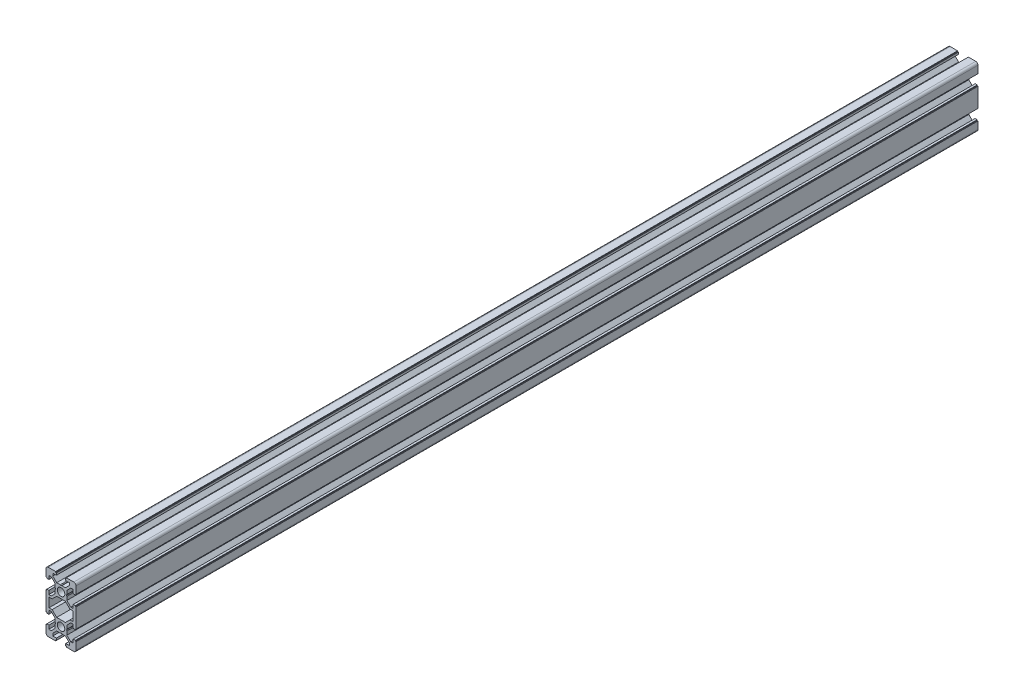
SolidWorks part; units mm, degrees
ref_plane "前视基准面" through (0, 0, 0) normal (0, 0, 1) x (1, 0, 0)
ref_plane "上视基准面" through (0, 0, 0) normal (0, 1, 0) x (1, 0, 0)
ref_plane "右视基准面" through (0, 0, 0) normal (1, 0, 0) x (0, 0, -1)
sketch "草图30" plane through (0, 0, 0) normal (0, 0, 1) x (1, 0, 0)
  line B0 (-7.4456, 0) -> (7.4456, 0) construction
  line B1 (0, -11.0182) -> (0, 30.6964) construction
  line B2 (-7.4456, 20) -> (7.4456, 20) construction
  line B3 (-10.5248, 9.8391) -> (10.5248, 9.8391) construction
  line B4 (5.9101, 6.9) -> (2.9101, 3.9)
  line B5 (2.9101, 3.9) -> (-2.9101, 3.9)
  line B6 (-2.9101, 3.9) -> (-5.9101, 6.9)
  line B7 (-5.9101, 6.9) -> (-8, 6.9)
  line B8 (-8, 6.9) -> (-8, 13.1)
  line B9 (-8, 13.1) -> (-5.9101, 13.1)
  line B10 (-5.9101, 13.1) -> (-2.9101, 16.1)
  line B11 (-2.9101, 16.1) -> (2.9101, 16.1)
  line B12 (2.9101, 16.1) -> (5.9101, 13.1)
  line B13 (5.9101, 13.1) -> (8, 13.1)
  line B14 (8, 13.1) -> (8, 6.9)
  line B15 (8, 6.9) -> (5.9101, 6.9)
  line B16 (-8.1, 14.5) -> (-8.1, 16.9)
  line B17 (-8.1, 16.9) -> (-9.5, 16.9)
  line B18 (-9.5, 16.9) -> (-9.5, 16.4)
  line B19 (-9.5, 16.4) -> (-10, 16.4)
  line B20 (-10, 16.4) -> (-10, 3.6)
  line B21 (-10, 3.6) -> (-9.5, 3.6)
  line B22 (-9.5, 3.6) -> (-9.5, 3.1)
  line B23 (-9.5, 3.1) -> (-8.1, 3.1)
  line B24 (-8.1, 3.1) -> (-8.1, 5.5)
  line B25 (-8.1, 5.5) -> (-6.4899, 5.5)
  line B26 (-6.4899, 5.5) -> (-3.9, 2.9101)
  line B27 (-3.9, 2.9101) -> (-3.9, 0.5196)
  line B28 (-3.9, 0.5196) -> (-3.6, 0)
  line B29 (-3.6, 0) -> (-3.9, -0.5196)
  line B30 (-3.9, -0.5196) -> (-3.9, -2.9101)
  line B31 (-3.9, -2.9101) -> (-6.4899, -5.5)
  line B32 (-6.4899, -5.5) -> (-8.1, -5.5)
  line B33 (-8.1, -5.5) -> (-8.1, -3.1)
  line B34 (-8.1, -3.1) -> (-9.5, -3.1)
  line B35 (-9.5, -3.1) -> (-9.5, -3.6)
  line B36 (-9.5, -3.6) -> (-10, -3.6)
  line B37 (-10, -3.6) -> (-10, -8.5)
  line B38 (-8.5, -10) -> (-3.6, -10)
  line B39 (-3.6, -10) -> (-3.6, -9.5)
  line B40 (-3.6, -9.5) -> (-3.1, -9.5)
  line B41 (-3.1, -9.5) -> (-3.1, -8.1)
  line B42 (-3.1, -8.1) -> (-5.5, -8.1)
  line B43 (-5.5, -8.1) -> (-5.5, -6.4899)
  line B44 (-5.5, -6.4899) -> (-2.9101, -3.9)
  line B45 (-2.9101, -3.9) -> (-0.5196, -3.9)
  line B46 (-0.5196, -3.9) -> (0, -3.6)
  line B47 (0, -3.6) -> (0.5196, -3.9)
  line B48 (0.5196, -3.9) -> (2.9101, -3.9)
  line B49 (2.9101, -3.9) -> (5.5, -6.4899)
  line B50 (5.5, -6.4899) -> (5.5, -8.1)
  line B51 (5.5, -8.1) -> (3.1, -8.1)
  line B52 (3.1, -8.1) -> (3.1, -9.5)
  line B53 (3.1, -9.5) -> (3.6, -9.5)
  line B54 (3.6, -9.5) -> (3.6, -10)
  line B55 (3.6, -10) -> (8.5, -10)
  line B56 (10, -8.5) -> (10, -3.6)
  line B57 (10, -3.6) -> (9.5, -3.6)
  line B58 (9.5, -3.6) -> (9.5, -3.1)
  line B59 (9.5, -3.1) -> (8.1, -3.1)
  line B60 (8.1, -3.1) -> (8.1, -5.5)
  line B61 (8.1, -5.5) -> (6.4899, -5.5)
  line B62 (6.4899, -5.5) -> (3.9, -2.9101)
  line B63 (3.9, -2.9101) -> (3.9, -0.5196)
  line B64 (3.9, -0.5196) -> (3.6, 0)
  line B65 (3.6, 0) -> (3.9, 0.5196)
  line B66 (3.9, 0.5196) -> (3.9, 2.9101)
  line B67 (3.9, 2.9101) -> (6.4899, 5.5)
  line B68 (6.4899, 5.5) -> (8.1, 5.5)
  line B69 (8.1, 5.5) -> (8.1, 3.1)
  line B70 (8.1, 3.1) -> (9.5, 3.1)
  line B71 (9.5, 3.1) -> (9.5, 3.6)
  line B72 (9.5, 3.6) -> (10, 3.6)
  line B73 (10, 3.6) -> (10, 16.4)
  line B74 (10, 16.4) -> (9.5, 16.4)
  line B75 (9.5, 16.4) -> (9.5, 16.9)
  line B76 (9.5, 16.9) -> (8.1, 16.9)
  line B77 (8.1, 16.9) -> (8.1, 14.5)
  line B78 (8.1, 14.5) -> (6.4899, 14.5)
  line B79 (6.4899, 14.5) -> (3.9, 17.0899)
  line B80 (3.9, 17.0899) -> (3.9, 19.4804)
  line B81 (3.9, 19.4804) -> (3.6, 20)
  line B82 (3.6, 20) -> (3.9, 20.5196)
  line B83 (3.9, 20.5196) -> (3.9, 22.9101)
  line B84 (3.9, 22.9101) -> (6.4899, 25.5)
  line B85 (6.4899, 25.5) -> (8.1, 25.5)
  line B86 (8.1, 25.5) -> (8.1, 23.1)
  line B87 (8.1, 23.1) -> (9.5, 23.1)
  line B88 (9.5, 23.1) -> (9.5, 23.6)
  line B89 (9.5, 23.6) -> (10, 23.6)
  line B90 (10, 23.6) -> (10, 28.5)
  line B91 (8.5, 30) -> (3.6, 30)
  line B92 (3.6, 30) -> (3.6, 29.5)
  line B93 (3.6, 29.5) -> (3.1, 29.5)
  line B94 (3.1, 29.5) -> (3.1, 28.1)
  line B95 (3.1, 28.1) -> (5.5, 28.1)
  line B96 (5.5, 28.1) -> (5.5, 26.4899)
  line B97 (5.5, 26.4899) -> (2.9101, 23.9)
  line B98 (2.9101, 23.9) -> (0.5196, 23.9)
  line B99 (0.5196, 23.9) -> (0, 23.6)
  line B100 (0, 23.6) -> (-0.5196, 23.9)
  line B101 (-0.5196, 23.9) -> (-2.9101, 23.9)
  line B102 (-2.9101, 23.9) -> (-5.5, 26.4899)
  line B103 (-5.5, 26.4899) -> (-5.5, 28.1)
  line B104 (-5.5, 28.1) -> (-3.1, 28.1)
  line B105 (-3.1, 28.1) -> (-3.1, 29.5)
  line B106 (-3.1, 29.5) -> (-3.6, 29.5)
  line B107 (-3.6, 29.5) -> (-3.6, 30)
  line B108 (-3.6, 30) -> (-8.5, 30)
  line B109 (-10, 28.5) -> (-10, 23.6)
  line B110 (-10, 23.6) -> (-9.5, 23.6)
  line B111 (-9.5, 23.6) -> (-9.5, 23.1)
  line B112 (-9.5, 23.1) -> (-8.1, 23.1)
  line B113 (-8.1, 23.1) -> (-8.1, 25.5)
  line B114 (-8.1, 25.5) -> (-6.4899, 25.5)
  line B115 (-6.4899, 25.5) -> (-3.9, 22.9101)
  line B116 (-3.9, 22.9101) -> (-3.9, 20.5196)
  line B117 (-3.9, 20.5196) -> (-3.6, 20)
  line B118 (-3.6, 20) -> (-3.9, 19.4804)
  line B119 (-3.9, 19.4804) -> (-3.9, 17.0899)
  line B120 (-3.9, 17.0899) -> (-6.4899, 14.5)
  line B121 (-6.4899, 14.5) -> (-8.1, 14.5)
  circle B122 centre (0, 20) radius 2.5
  circle B123 centre (0, 0) radius 2.5
  arc B124 (-10, -8.5) -> (-8.5, -10) centre (-8.5, -8.5) ccw
  arc B125 (8.5, -10) -> (10, -8.5) centre (8.5, -8.5) ccw
  arc B126 (10, 28.5) -> (8.5, 30) centre (8.5, 28.5) ccw
  arc B127 (-8.5, 30) -> (-10, 28.5) centre (-8.5, 28.5) ccw
sketch_block_instance "块3-1"
sketch_block "块3"
extrude "凸台-拉伸3" add sketch "草图30" along normal blind 600
cosmetic thread "装饰螺纹线1" [suppressed]
cosmetic thread "装饰螺纹线2" [suppressed]
cosmetic thread "装饰螺纹线3" [suppressed]
cosmetic thread "装饰螺纹线4" [suppressed]
ref_plane "基准面1" through (0, 0, 600) normal (0, 0, 1) x (1, 0, 0)
ref_plane "基准面2" through (0, 30, 0) normal (0, 1, 0) x (1, 0, 0)
ref_plane "基准面3" through (0, -10, 0) normal (0, 1, 0) x (1, 0, 0)
ref_plane "基准面4" through (10, 0, 0) normal (1, 0, 0) x (0, 0, -1)
ref_plane "基准面5" through (-10, 0, 0) normal (1, 0, 0) x (0, 0, -1)
sketch "草图19" plane through (0, 0, 0) normal (0, 0, 1) x (1, 0, 0)
  line L0 (0, 0) -> (0, 11.6901) construction
  line L1 (0, 0) -> (10.3437, 0) construction
sketch "草图20" plane through (0, 0, 0) normal (0, 1, 0) x (1, 0, 0)
  line L0 (0, 0) -> (0, 3.5576) construction
ref_point "点1"
sketch "草图2" [suppressed] plane through (0, 0, 0) normal (1, 0, 0) x (0, 0, -1)
  line L0 (-280, -10) -> (-240, 30)
  line L1 (16.5, -10) -> (-16.5, -10) construction
  line L2 (16.5, 30) -> (-16.5, 30) construction
  line L3 (-240, 30) -> (-280, 30)
  line L4 (-280, 16.5) -> (-280, -16.5) construction
  line L5 (-280, 30) -> (-280, -10)
  dimension "D1" = 45
extrude "切除-拉伸1" [suppressed] cut sketch "草图2" against normal through all and the other way through all
sketch "草图3" [suppressed] plane through (0, 0, 0) normal (1, 0, 0) x (0, 0, -1)
  line L0 (0, -10) -> (-40, 30)
  line L1 (16.5, -10) -> (-16.5, -10) construction
  line L2 (16.5, 30) -> (-16.5, 30) construction
  line L3 (-40, 30) -> (0, 30)
  line L4 (0, 30) -> (0, -10)
  line L5 (0, 11.189) -> (0, -11.189) construction
  dimension "D1" = 45
extrude "切除-拉伸2" [suppressed] cut sketch "草图3" against normal through all and the other way through all
sketch "草图4" [suppressed] plane through (0, 0, 0) normal (1, 0, 0) x (0, 0, -1)
  line L0 (-280, 30) -> (-240, -10)
  line L1 (16.5, 30) -> (-16.5, 30) construction
  line L2 (-280, 16.5) -> (-280, -16.5) construction
  line L3 (16.5, -10) -> (-16.5, -10) construction
  line L4 (-240, -10) -> (-280, -10)
  line L5 (-280, -10) -> (-280, 30)
  dimension "D1" = 45
extrude "切除-拉伸3" [suppressed] cut sketch "草图4" against normal through all and the other way through all
sketch "草图5" [suppressed] plane through (0, 0, 0) normal (1, 0, 0) x (0, 0, -1)
  line L0 (0, 30) -> (-40, -10)
  line L1 (16.5, 30) -> (-16.5, 30) construction
  line L2 (16.5, -10) -> (-16.5, -10) construction
  line L3 (-40, -10) -> (0, -10)
  line L4 (0, -10) -> (0, 30)
  line L5 (0, 11.189) -> (0, -11.189) construction
  dimension "D1" = 45
extrude "切除-拉伸4" [suppressed] cut sketch "草图5" against normal through all and the other way through all
sketch "草图6" [suppressed] plane through (0, 0, 0) normal (0, 1, 0) x (1, 0, 0)
  line L0 (-10, -280) -> (10, -260)
  line L1 (-10, -16.5) -> (-10, 16.5) construction
  line L2 (-16.5, -280) -> (16.5, -280) construction
  line L3 (10, -16.5) -> (10, 16.5) construction
  line L4 (10, -260) -> (10, -280)
  line L5 (10, -280) -> (-10, -280)
  dimension "D1" = 45
extrude "切除-拉伸5" [suppressed] cut sketch "草图6" against normal through all and the other way through all
sketch "草图7" [suppressed] plane through (0, 0, 0) normal (0, 1, 0) x (1, 0, 0)
  line L0 (-10, 0) -> (10, -20)
  line L1 (-10, -16.5) -> (-10, 16.5) construction
  line L2 (10, -16.5) -> (10, 16.5) construction
  line L3 (10, -20) -> (10, 0)
  line L4 (-11.189, 0) -> (11.189, 0) construction
  line L5 (10, 0) -> (-10, 0)
  dimension "D1" = 45
extrude "切除-拉伸6" [suppressed] cut sketch "草图7" against normal through all and the other way through all
sketch "草图8" [suppressed] plane through (0, 0, 0) normal (0, 1, 0) x (1, 0, 0)
  line L0 (-10, -260) -> (10, -280)
  line L1 (-10, -16.5) -> (-10, 16.5) construction
  line L2 (10, -16.5) -> (10, 16.5) construction
  line L3 (-16.5, -280) -> (16.5, -280) construction
  line L4 (10, -280) -> (-10, -280)
  line L5 (-10, -280) -> (-10, -260)
  dimension "D1" = 45
extrude "切除-拉伸7" [suppressed] cut sketch "草图8" against normal through all and the other way through all
sketch "草图9" [suppressed] plane through (0, 0, 0) normal (0, 1, 0) x (1, 0, 0)
  line L0 (10, 0) -> (-10, -20)
  line L1 (10, -16.5) -> (10, 16.5) construction
  line L2 (-11.189, 0) -> (11.189, 0) construction
  line L3 (-10, -16.5) -> (-10, 16.5) construction
  line L4 (-10, -20) -> (-10, 0)
  line L5 (-10, 0) -> (10, 0)
  dimension "D1" = 45
extrude "切除-拉伸8" [suppressed] cut sketch "草图9" against normal through all and the other way through all
sketch "草图10" [suppressed] plane through (10, -3.64, 139.7) normal (1, 0, 0) x (0, 0, -1)
  line L1 (-140.3, 14.829) -> (-140.3, -7.549) construction
  circle A0 centre (-127.3, 3.64) radius 6.25
  dimension "D1" = 12.5
  dimension "D2" = 13
extrude "切除-拉伸9" [suppressed] cut sketch "草图10" against normal blind 9
pattern_linear "阵列(线性)1" [suppressed] count 2 spacing 20 along (0, 1, 0)
sketch "草图11" [suppressed] plane through (10, 0, 0) normal (1, 0, 0) x (0, 0, -1)
  circle A0 centre (-13, 0) radius 6.25
  dimension "D1" = 12.5
  dimension "D2" = 13
extrude "切除-拉伸10" [suppressed] cut sketch "草图11" against normal blind 9
pattern_linear "阵列(线性)2" [suppressed] count 2 spacing 20 along (0, 1, 0)
sketch "草图12" [suppressed] plane through (0, 0, 0) normal (0, 1, 0) x (1, 0, 0)
  line L0 (-10, -22) -> (-10, 22) construction
  line L1 (-10, -267) -> (-1, -267)
  line L2 (-10, -267) -> (-10, -260.75)
  line L3 (-10, -260.75) -> (-1, -260.75)
  line L4 (-1, -267) -> (-1, -260.75)
  line L5 (10, -22) -> (10, 22) construction
  line L6 (10, -267) -> (1, -267)
  line L7 (10, -267) -> (10, -260.75)
  line L8 (10, -260.75) -> (1, -260.75)
  line L9 (1, -267) -> (1, -260.75)
  line L10 (-11.189, -280) -> (11.189, -280) construction
  dimension "D1" = 13
  dimension "D2" = 6.25
  dimension "D3" = 9
revolve "切除-旋转1" [suppressed] cut sketch "草图12" angle 360 about L1
pattern_linear "阵列(线性)4" [suppressed] count 2 spacing 20 along (0, 1, 0)
sketch "草图13" [suppressed] plane through (0, 0, 0) normal (0, 1, 0) x (1, 0, 0)
  line L0 (-10, -22) -> (-10, 22) construction
  line L1 (-10, -19.25) -> (-1, -19.25)
  line L2 (-10, -19.25) -> (-10, -13)
  line L3 (-10, -13) -> (-1, -13)
  line L4 (-1, -19.25) -> (-1, -13)
  line L5 (10, -22) -> (10, 22) construction
  line L6 (10, -19.25) -> (1, -19.25)
  line L7 (10, -19.25) -> (10, -13)
  line L8 (10, -13) -> (1, -13)
  line L9 (1, -19.25) -> (1, -13)
  dimension "D1" = 13
  dimension "D2" = 6.25
  dimension "D3" = 9
revolve "切除-旋转2" [suppressed] cut sketch "草图13" angle 360 about L3
pattern_linear "阵列(线性)5" [suppressed] count 2 spacing 20 along (0, 1, 0)
sketch "草图14" [suppressed] plane through (0, 30, 0) normal (0, 1, 0) x (1, 0, 0)
  line L0 (-11.189, -280) -> (11.189, -280) construction
  circle A0 centre (0, -267) radius 6.25
  dimension "D1" = 12.5
  dimension "D2" = 13
extrude "切除-拉伸11" [suppressed] cut sketch "草图14" against normal blind 9
sketch "草图15" [suppressed] plane through (0, 30, 0) normal (0, 1, 0) x (1, 0, 0)
  line L0 (-11.189, 0) -> (11.189, 0) construction
  circle A0 centre (0, -13) radius 6.25
  dimension "D1" = 12.5
  dimension "D2" = 13
extrude "切除-拉伸12" [suppressed] cut sketch "草图15" against normal blind 9
sketch "草图16" [suppressed] plane through (0, 0, 0) normal (1, 0, 0) x (0, 0, -1)
  line L0 (11.189, 30) -> (-11.189, 30) construction
  line L1 (-267, 30) -> (-260.75, 30)
  line L2 (-267, 30) -> (-267, 21)
  line L3 (-267, 21) -> (-260.75, 21)
  line L4 (-260.75, 30) -> (-260.75, 21)
  line L5 (11.189, -10) -> (-11.189, -10) construction
  line L6 (-267, -10) -> (-260.75, -10)
  line L7 (-267, -10) -> (-267, -1)
  line L8 (-267, -1) -> (-260.75, -1)
  line L9 (-260.75, -10) -> (-260.75, -1)
  line L10 (-280, 11.189) -> (-280, -11.189) construction
  dimension "D1" = 9
  dimension "D2" = 6.25
  dimension "D3" = 13
revolve "切除-旋转3" [suppressed] cut sketch "草图16" angle 360 about L2
sketch "草图17" [suppressed] plane through (0, 0, 0) normal (1, 0, 0) x (0, 0, -1)
  line L0 (11.189, 30) -> (-11.189, 30) construction
  line L1 (-13, 30) -> (-19.25, 30)
  line L2 (-13, 30) -> (-13, 21)
  line L3 (-13, 21) -> (-19.25, 21)
  line L4 (-19.25, 30) -> (-19.25, 21)
  line L5 (11.189, -10) -> (-11.189, -10) construction
  line L6 (-13, -10) -> (-19.25, -10)
  line L7 (-13, -10) -> (-13, -1)
  line L8 (-13, -1) -> (-19.25, -1)
  line L9 (-19.25, -10) -> (-19.25, -1)
  dimension "D1" = 6.25
  dimension "D2" = 9
  dimension "D3" = 13
revolve "切除-旋转4" [suppressed] cut sketch "草图17" angle 360 about L2
sketch "草图18" [suppressed] plane through (0, 0, 0) normal (0, 1, 0) x (1, 0, 0)
  line L0 (-10, -230) -> (10, -230)
  line L1 (-10, -22) -> (-10, 22) construction
  line L2 (10, -22) -> (10, 22) construction
  line L3 (10, -230) -> (10, -224.5)
  line L4 (10, -224.5) -> (3.5, -224.5)
  line L5 (3.5, -224.5) -> (3.5, -226.75)
  line L6 (3.5, -226.75) -> (-10, -226.75)
  line L7 (-10, -226.75) -> (-10, -230)
  line L8 (-11.189, -280) -> (11.189, -280) construction
  dimension "D1" = 50
  dimension "D2" = 5.5
  dimension "D3" = 3.25
  dimension "D4" = 6.5
revolve "切除-旋转5" [suppressed] cut sketch "草图18" angle 360 about L0
pattern_linear "阵列(线性)6" [suppressed] count 2 spacing 20 along (0, 1, 0)
other "表格阵列1" [suppressed] parameters "D0"=70, "D1"=10, "D2"=90, "D3"=10, "D4"=110, "D5"=10, "D6"=130, "D7"=10
sketch "草图21" [suppressed] plane through (0, 0, 0) normal (0, 1, 0) x (1, 0, 0)
  line L0 (-10, -50) -> (10, -50)
  line L1 (-10, -22) -> (-10, 22) construction
  line L2 (10, -22) -> (10, 22) construction
  line L3 (10, -50) -> (10, -55.5)
  line L4 (10, -55.5) -> (3.5, -55.5)
  line L5 (3.5, -55.5) -> (3.5, -53.25)
  line L6 (3.5, -53.25) -> (-10, -53.25)
  line L7 (-10, -53.25) -> (-10, -50)
  dimension "D1" = 5.5
  dimension "D2" = 3.25
  dimension "D3" = 6.5
  dimension "D4" = 50
revolve "切除-旋转6" [suppressed] cut sketch "草图21" angle 360 about L0
pattern_linear "阵列(线性)7" [suppressed] count 2 spacing 20 along (0, 1, 0)
other "表格阵列2" [suppressed] parameters "D0"=70, "D1"=10, "D2"=90, "D3"=10, "D4"=110, "D5"=10, "D6"=130, "D7"=10
sketch "草图22" [suppressed] plane through (0, 0, 0) normal (1, 0, 0) x (0, 0, -1)
  line L0 (-230, 30) -> (-230, -10)
  line L1 (11.189, 30) -> (-11.189, 30) construction
  line L2 (11.189, -10) -> (-11.189, -10) construction
  line L3 (-230, -10) -> (-226.75, -10)
  line L4 (-226.75, -10) -> (-226.75, 23.5)
  line L5 (-226.75, 23.5) -> (-224.5, 23.5)
  line L6 (-224.5, 23.5) -> (-224.5, 30)
  line L7 (-224.5, 30) -> (-230, 30)
  line L8 (-280, 11.189) -> (-280, -11.189) construction
  dimension "D1" = 5.5
  dimension "D2" = 3.25
  dimension "D3" = 6.5
  dimension "D4" = 50
revolve "切除-旋转7" [suppressed] cut sketch "草图22" angle 360 about L0
other "表格阵列3" [suppressed] parameters "D0"=70, "D1"=0, "D2"=90, "D3"=0, "D4"=110, "D5"=0, "D6"=130, "D7"=0
sketch "草图23" [suppressed] plane through (0, 0, 0) normal (1, 0, 0) x (0, 0, -1)
  line L0 (-50, 30) -> (-55.5, 30)
  line L1 (11.189, 30) -> (-11.189, 30) construction
  line L2 (-55.5, 30) -> (-55.5, 23.5)
  line L3 (-55.5, 23.5) -> (-53.25, 23.5)
  line L4 (-53.25, 23.5) -> (-53.25, -10)
  line L5 (11.189, -10) -> (-11.189, -10) construction
  line L6 (-53.25, -10) -> (-50, -10)
  line L7 (-50, -10) -> (-50, 30)
  dimension "D1" = 5.5
  dimension "D2" = 3.25
  dimension "D3" = 6.5
  dimension "D4" = 50
revolve "切除-旋转8" [suppressed] cut sketch "草图23" angle 360 about L7
other "表格阵列4" [suppressed] parameters "D0"=70, "D1"=0, "D2"=90, "D3"=0, "D4"=110, "D5"=0, "D6"=130, "D7"=0
sketch "草图24" [suppressed] plane through (10, 0, 0) normal (1, 0, 0) x (0, 0, -1)
  line L0 (-280, 11.189) -> (-280, -11.189) construction
  circle A0 centre (-240, 0) radius 3.25
  dimension "D1" = 6.5
  dimension "D2" = 40
extrude "切除-拉伸13" [suppressed] cut sketch "草图24" against normal through all
pattern_linear "阵列(线性)8" [suppressed] count 2 spacing 20 along (0, 1, 0)
other "表格阵列5" [suppressed] parameters "D0"=60, "D1"=10, "D2"=80, "D3"=10, "D4"=100, "D5"=10, "D6"=120, "D7"=10
sketch "草图25" [suppressed] plane through (10, 0, 0) normal (1, 0, 0) x (0, 0, -1)
  circle A0 centre (-40, 0) radius 3.25
  dimension "D1" = 6.5
  dimension "D2" = 40
extrude "切除-拉伸14" [suppressed] cut sketch "草图25" against normal through all
pattern_linear "阵列(线性)9" [suppressed] count 2 spacing 20 along (0, 1, 0)
other "表格阵列6" [suppressed] parameters "D0"=60, "D1"=10, "D2"=80, "D3"=10, "D4"=100, "D5"=10, "D6"=120, "D7"=10
sketch "草图26" [suppressed] plane through (0, 30, 0) normal (0, 1, 0) x (1, 0, 0)
  line L0 (-11.189, -280) -> (11.189, -280) construction
  circle A0 centre (0, -240) radius 3.25
  dimension "D1" = 6.5
  dimension "D2" = 40
extrude "切除-拉伸15" [suppressed] cut sketch "草图26" against normal through all
other "表格阵列7" [suppressed] parameters "D0"=60, "D1"=0, "D2"=80, "D3"=0, "D4"=100, "D5"=0, "D6"=120, "D7"=0
sketch "草图27" [suppressed] plane through (0, 30, 0) normal (0, 1, 0) x (1, 0, 0)
  circle A0 centre (0, -40) radius 3.25
  dimension "D1" = 6.5
  dimension "D2" = 40
extrude "切除-拉伸16" [suppressed] cut sketch "草图27" against normal through all
other "表格阵列8" [suppressed] parameters "D0"=60, "D1"=0, "D2"=80, "D3"=0, "D4"=100, "D5"=0, "D6"=120, "D7"=0
sketch "草图31" [suppressed] plane through (0, 0, 0) normal (0, 1, 0) x (1, 0, 0)
  line L0 (-10, -230) -> (-10, -224.5)
  line L1 (-10, -224.5) -> (-3.5, -224.5)
  line L2 (-3.5, -224.5) -> (-3.5, -226.75)
  line L3 (-3.5, -226.75) -> (10, -226.75)
  line L4 (10, -226.75) -> (10, -230)
  line L5 (10, -230) -> (-10, -230)
  line L6 (-10, -22) -> (-10, 22) construction
  line L7 (10, -22) -> (10, 22) construction
  line L8 (-11.189, -280) -> (11.189, -280) construction
  dimension "D1" = 3.25
  dimension "D2" = 5.5
  dimension "D3" = 6.5
  dimension "D4" = 50
revolve "切除-旋转9" [suppressed] cut sketch "草图31" angle 360 about L5
pattern_linear "阵列(线性)10" [suppressed] count 2 spacing 20
other "表格阵列9" [suppressed] parameters "D0"=70, "D1"=10, "D2"=90, "D3"=10, "D4"=110, "D5"=10, "D6"=130, "D7"=10
sketch "草图32" [suppressed] plane through (0, 0, 0) normal (0, 1, 0) x (1, 0, 0)
  line L0 (10, -50) -> (10, -53.25)
  line L1 (10, -53.25) -> (-3.5, -53.25)
  line L2 (-3.5, -53.25) -> (-3.5, -55.5)
  line L3 (-3.5, -55.5) -> (-10, -55.5)
  line L4 (-10, -55.5) -> (-10, -50)
  line L5 (-10, -50) -> (10, -50)
  line L6 (-10, -22) -> (-10, 22) construction
  line L7 (10, -22) -> (10, 22) construction
  dimension "D1" = 5.5
  dimension "D2" = 6.5
  dimension "D3" = 3.25
  dimension "D4" = 50
revolve "切除-旋转10" [suppressed] cut sketch "草图32" angle 360 about L5
pattern_linear "阵列(线性)11" [suppressed] count 2 spacing 20
other "表格阵列10" [suppressed] parameters "D0"=20, "D1"=0, "D2"=40, "D3"=0, "D4"=60, "D5"=0, "D6"=80, "D7"=0
sketch "草图33" [suppressed] plane through (0, 0, 0) normal (1, 0, 0) x (0, 0, -1)
  line L0 (-230, 30) -> (-226.75, 30)
  line L1 (-226.75, 30) -> (-226.75, -3.5)
  line L2 (-226.75, -3.5) -> (-224.5, -3.5)
  line L3 (-224.5, -3.5) -> (-224.5, -10)
  line L4 (-224.5, -10) -> (-230, -10)
  line L5 (-230, -10) -> (-230, 30)
  line L6 (11.189, -10) -> (-11.189, -10) construction
  line L7 (11.189, 30) -> (-11.189, 30) construction
  line L8 (-280, 11.189) -> (-280, -11.189) construction
  dimension "D1" = 3.25
  dimension "D2" = 5.5
  dimension "D3" = 6.5
  dimension "D4" = 50
revolve "切除-旋转11" [suppressed] cut sketch "草图33" angle 360 about L5
other "表格阵列11" [suppressed] parameters "D0"=70, "D1"=0, "D2"=90, "D3"=0, "D4"=110, "D5"=0, "D6"=130, "D7"=0
sketch "草图34" [suppressed] plane through (0, 0, 0) normal (1, 0, 0) x (0, 0, -1)
  line L0 (-50, 30) -> (-53.25, 30)
  line L1 (-53.25, 30) -> (-53.25, -3.5)
  line L2 (-53.25, -3.5) -> (-55.5, -3.5)
  line L3 (-55.5, -3.5) -> (-55.5, -10)
  line L4 (-55.5, -10) -> (-50, -10)
  line L5 (-50, -10) -> (-50, 30)
  line L6 (11.189, -10) -> (-11.189, -10) construction
  line L7 (11.189, 30) -> (-11.189, 30) construction
  dimension "D1" = 3.25
  dimension "D2" = 5.5
  dimension "D3" = 6.5
  dimension "D4" = 50
revolve "切除-旋转12" [suppressed] cut sketch "草图34" angle 360 about L5
other "表格阵列13" [suppressed] parameters "D0"=70, "D1"=0, "D2"=90, "D3"=0, "D4"=110, "D5"=0, "D6"=130, "D7"=0
